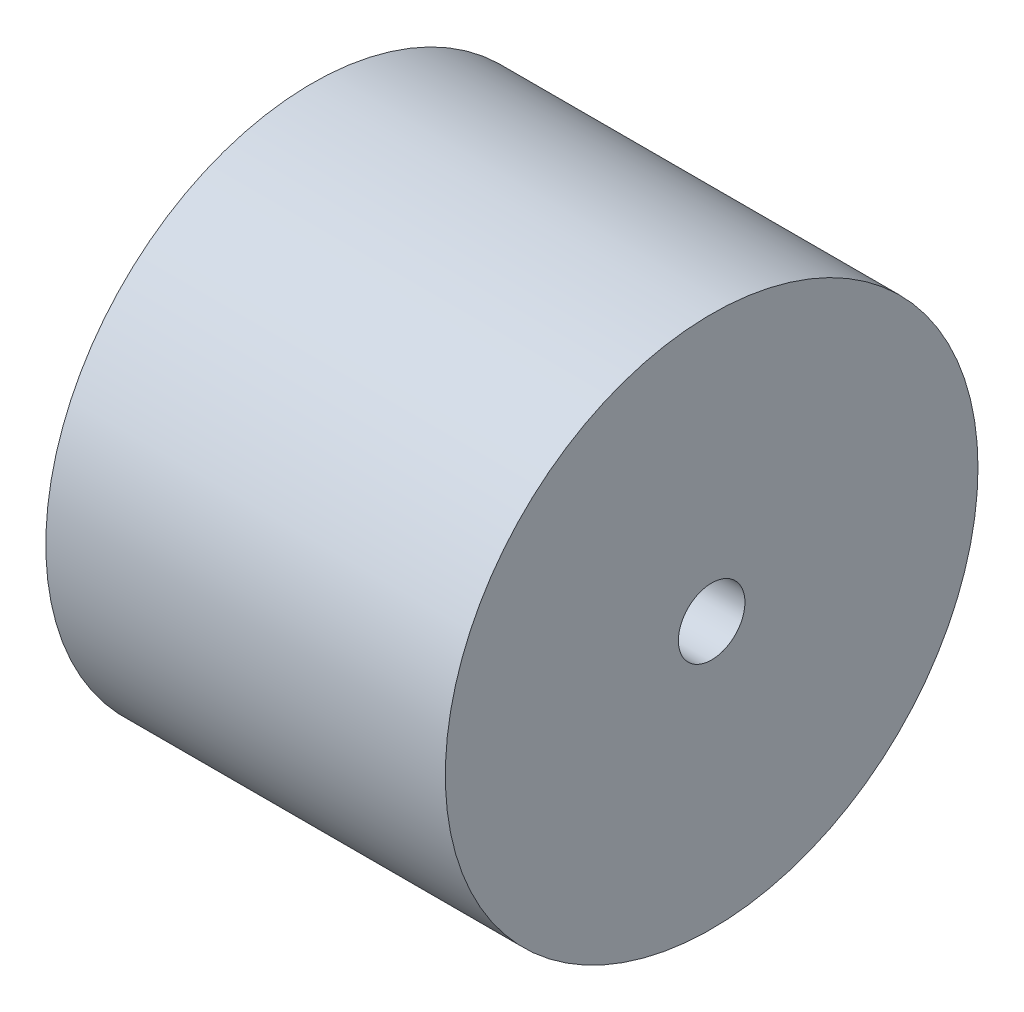
SolidWorks part; units mm, degrees
material "Plain Carbon Steel"
ref_plane "Front Plane" through (0, 0, 0) normal (0, 0, 1) x (1, 0, 0)
ref_plane "Top Plane" through (0, 0, 0) normal (0, 1, 0) x (1, 0, 0)
ref_plane "Right Plane" through (0, 0, 0) normal (1, 0, 0) x (0, 0, -1)
sketch "Sketch1" plane through (0, 0, 0) normal (0, 0, 1) x (1, 0, 0)
  line L0 (0, 0) -> (0, 10)
  line L1 (0, 10) -> (-15, 10)
  line L2 (-15, 10) -> (-15, 8.5)
  line L3 (-15, 8.5) -> (-15, 4) construction
  line L4 (-15, 4) -> (-15, 0)
  line L5 (-15, 0) -> (0, 0) construction
  line L6 (0, 0) -> (-15, 0)
  arc A0 (-15, 8.5) -> (-15, 4) centre (-19.4651, 6.25) cw
  dimension "D5" = 5
  dimension "D1" = 15
  dimension "D2" = 20
  dimension "D3" = 1.5
  dimension "D4" = 8
revolve "Revolve1" add sketch "Sketch1" angle 360 about L6
hole_wizard "M3 Tapped Hole1" positions "Sketch3" profile "Sketch2" tap size "M3" standard "DIN"
sketch "Sketch3" plane through (0, 0, 0) normal (1, 0, 0) x (0, 0, -1)
  point P0 (0, 0)
sketch "Sketch2" plane through (0, 0, 0) normal (0, 1, 0) x (0, 0, -1)
  line L0 (0, 0) -> (0, 8.2511)
  line L1 (0, 8.2511) -> (1.25, 7.5)
  line L2 (1.25, 7.5) -> (1.25, 0)
  line L5 (1.25, 0) -> (0, 0)
  line L10 (0, 8.2511) -> (-1.25, 7.5) construction
  line L11 (0, -6.35) -> (0, 107.95) construction
  dimension "Tap Drill Dia." = 2.5
  dimension "Tap Drill Depth" = 7.5
  dimension "Drill Angle" = 118
cosmetic thread "Hole Thread1" parameters "D1"=6, "D2"=3
